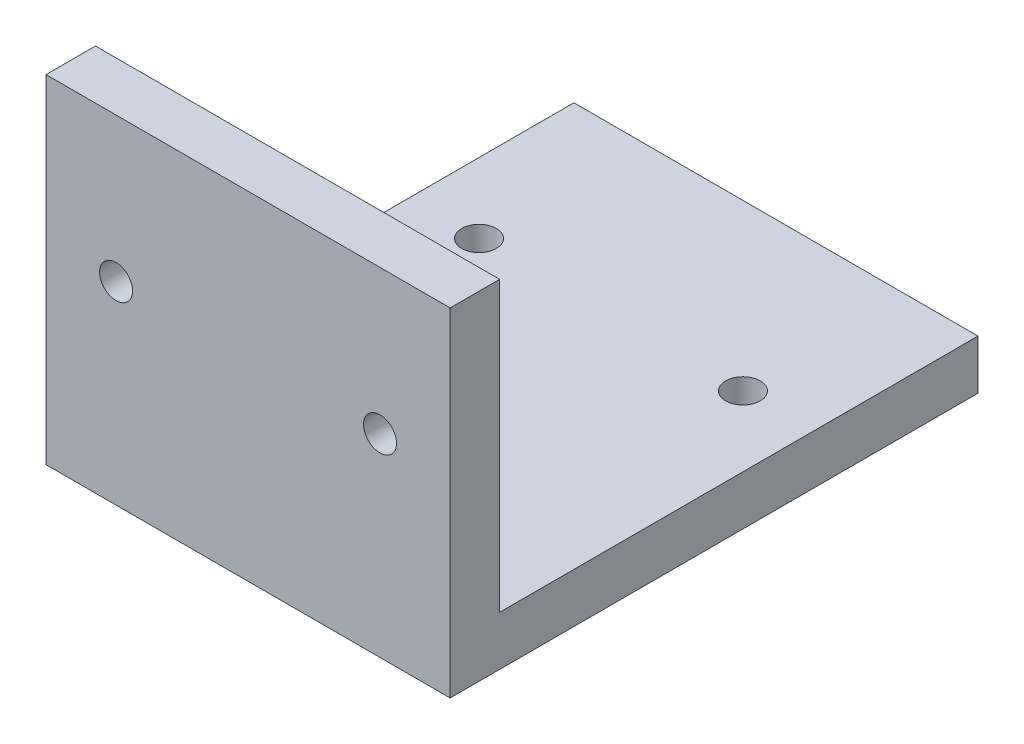
SolidWorks part; units mm, degrees
ref_plane "Front Plane" through (0, 0, 0) normal (0, 0, 1) x (1, 0, 0)
ref_plane "Top Plane" through (0, 0, 0) normal (0, 1, 0) x (1, 0, 0)
ref_plane "Right Plane" through (0, 0, 0) normal (1, 0, 0) x (0, 0, -1)
sketch "Sketch1" plane through (0, 0, 0) normal (0, 1, 0) x (1, 0, 0)
  line L0 (-12.25, 0) -> (12.25, 0) construction
  line L1 (-12.25, 16) -> (12.25, 16)
  line L2 (-12.25, 16) -> (-12.25, -16)
  line L3 (-12.25, -16) -> (12.25, -16)
  line L4 (12.25, 16) -> (12.25, -16)
  line L5 (-12.25, 16) -> (12.25, -16) construction
  line L6 (-12.25, -16) -> (12.25, 16) construction
  line L7 (0, 16) -> (0, -16) construction
  circle A0 centre (8, 6) radius 1.05
  circle A1 centre (-8, 6) radius 1.05
  point P0 (0, 0)
  dimension "D4" = 6
  dimension "D5" = 2.1
  dimension "D6" = 2.1
  dimension "D7" = 8
  dimension "D1" = 24.5
  dimension "D2" = 32
  dimension "D3" = 8
extrude "Boss-Extrude1" add sketch "Sketch1" along normal blind 3
sketch "Sketch3" plane through (0, 3, 0) normal (0, 1, 0) x (1, 0, 0)
  line L0 (12.25, -16) -> (12.25, 16) construction
  line L1 (-12.25, -16) -> (12.25, -16)
  line L2 (-12.25, -16) -> (-12.25, -13)
  line L3 (-12.25, -13) -> (12.25, -13)
  line L4 (12.25, -16) -> (12.25, -13)
  dimension "D1" = 3
extrude "Boss-Extrude3" add sketch "Sketch3" along normal blind 17.48
sketch "Sketch4" plane through (0, 0, 13) normal (0, 0, -1) x (-1, 0, 0)
  line L0 (0, 20.48) -> (0, 3) construction
  line L1 (-12.25, 20.48) -> (12.25, 20.48) construction
  line L2 (-12.25, 3) -> (12.25, 3) construction
  line L4 (12.25, 20.48) -> (12.25, 3) construction
  line L5 (12.25, 11.74) -> (-12.25, 11.74) construction
  line L6 (-12.25, 20.48) -> (-12.25, 3) construction
  circle A0 centre (8, 11.74) radius 1
  circle A1 centre (-8, 11.74) radius 1
  dimension "D2" = 2
  dimension "D1" = 8
extrude "Cut-Extrude1" cut sketch "Sketch4" against normal blind 10
sketch "Sketch5" plane through (0, 0, 13) normal (0, 0, -1) x (-1, 0, 0)
  line L0 (0, 3) -> (0, 20.48) construction
  line L1 (-12.25, 3) -> (12.25, 3) construction
  line L2 (-12.25, 20.48) -> (12.25, 20.48) construction
